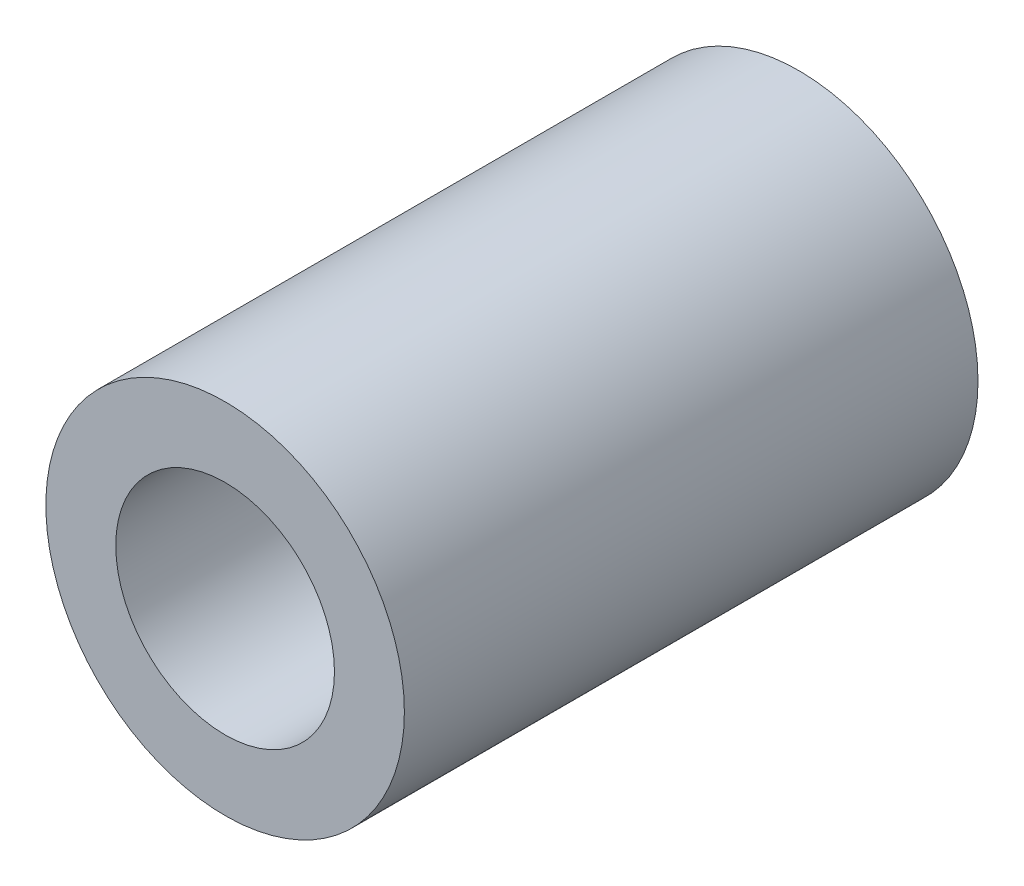
SolidWorks part; units mm, degrees
ref_plane "Ön Düzlem" through (0, 0, 0) normal (0, 0, 1) x (1, 0, 0)
ref_plane "Üst Düzlem" through (0, 0, 0) normal (0, 1, 0) x (1, 0, 0)
ref_plane "Sağ Düzlem" through (0, 0, 0) normal (1, 0, 0) x (0, 0, -1)
sketch "Sketch1" plane through (0, 0, 0) normal (0, 0, 1) x (1, 0, 0)
  circle A0 centre (0, 0) radius 3.05
  circle A1 centre (0, 0) radius 5
  dimension "D1" = 6.1
  dimension "D2" = 10
extrude "Boss-Extrude1" add sketch "Sketch1" along normal blind 16
